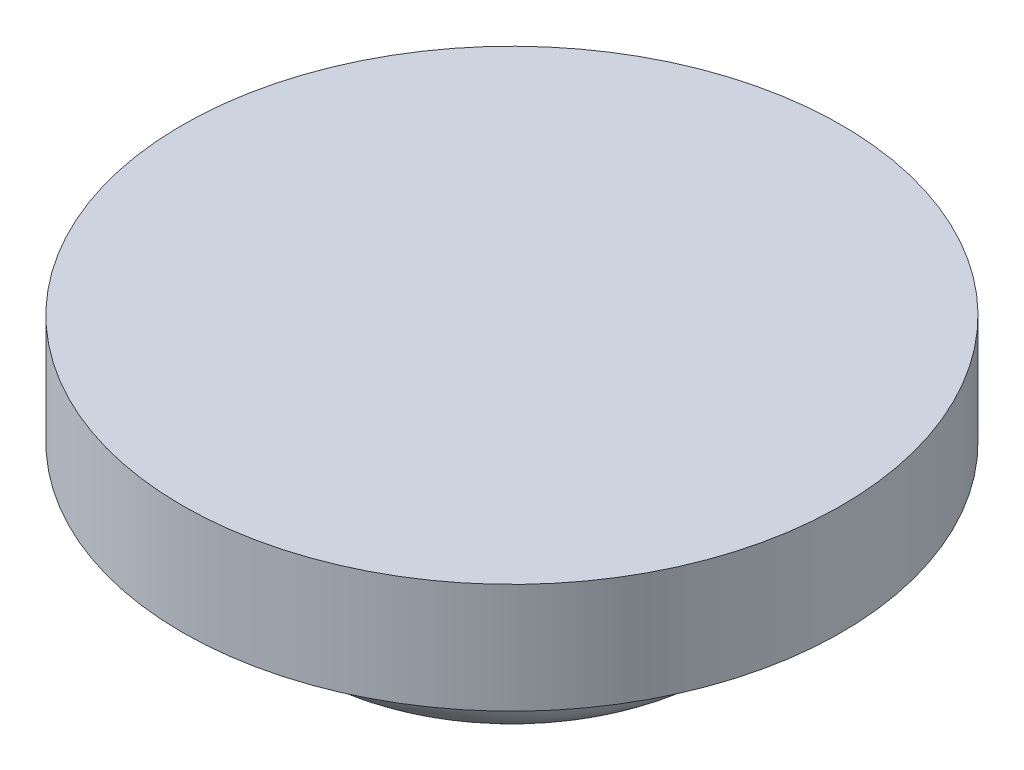
SolidWorks part; units mm, degrees
ref_plane "Płaszczyzna przednia" through (0, 0, 0) normal (0, 0, 1) x (1, 0, 0)
ref_plane "Płaszczyzna górna" through (0, 0, 0) normal (0, 1, 0) x (1, 0, 0)
ref_plane "Płaszczyzna prawa" through (0, 0, 0) normal (1, 0, 0) x (0, 0, -1)
sketch "Szkic1" plane through (0, 0, 0) normal (0, 1, 0) x (1, 0, 0)
  circle A0 centre (0, 0) radius 10
  dimension "D1" = 20
extrude "Dodanie-wyciągnięcie1" add sketch "Szkic1" along normal blind 5
fillet "Zaokrąglenie3" radius 2 1 edges at (0, 0, 10)
sketch "Szkic2" plane through (0, 5, 0) normal (0, 1, 0) x (1, 0, 0)
  circle A0 centre (0, 0) radius 15
  dimension "D1" = 30
extrude "Dodanie-wyciągnięcie2" add sketch "Szkic2" along normal blind 5
sketch "Szkic orientacji" plane through (0, 5, 0) normal (0, -1, 0) x (-1, 0, 0)
  circle A0 centre (0, 0) radius 10 construction
  circle A1 centre (0, 0) radius 15 construction
  circle A2 centre (0, 0) radius 10
  circle A3 centre (0, 0) radius 15 construction
  point P6 (0, 0)
other "Narzędzie formowania1"
